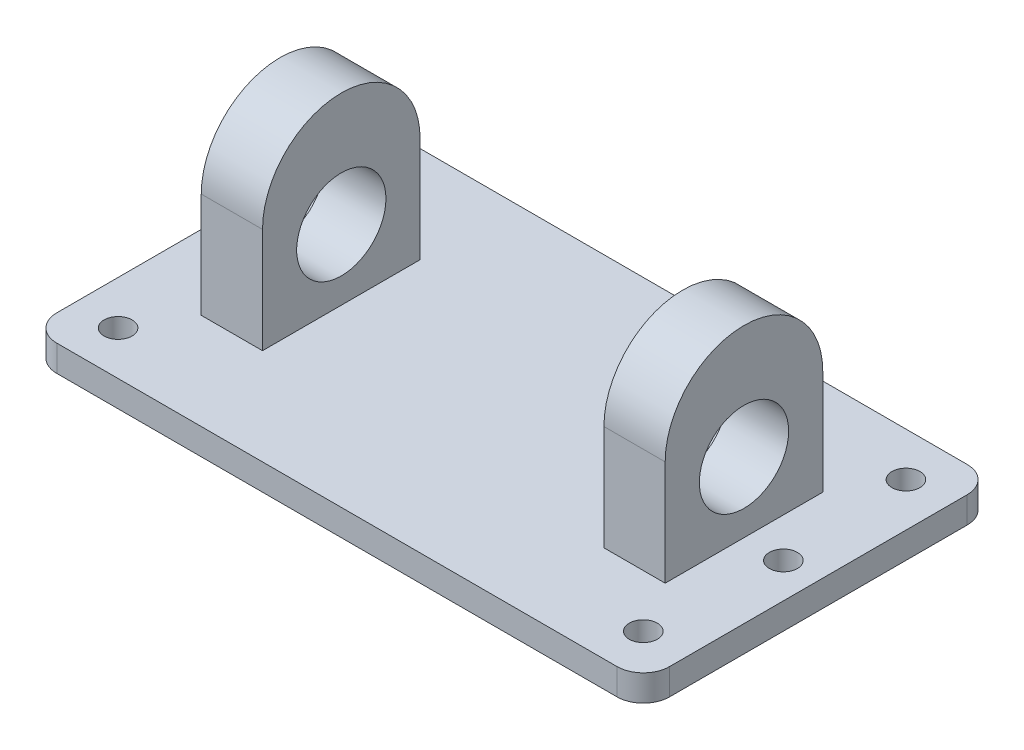
SolidWorks part; units mm, degrees
material "7050-T73510"
ref_plane "前视基准面" through (0, 0, 0) normal (0, 0, 1) x (1, 0, 0)
ref_plane "上视基准面" through (0, 0, 0) normal (0, 1, 0) x (1, 0, 0)
ref_plane "右视基准面" through (0, 0, 0) normal (1, 0, 0) x (0, 0, -1)
sketch "草图1" plane through (0, 0, 0) normal (0, 1, 0) x (1, 0, 0)
  line L1 (-32, -20) -> (32, -20)
  line L2 (-35, -17) -> (-35, 17)
  line L3 (-32, 20) -> (32, 20)
  line L4 (35, -17) -> (35, 17)
  line L5 (-35, -20) -> (35, 20) construction
  line L6 (-35, 20) -> (35, -20) construction
  arc A0 (32, -20) -> (35, -17) centre (32, -17) ccw
  arc A1 (-35, 17) -> (-32, 20) centre (-32, 17) cw
  arc A2 (-32, -20) -> (-35, -17) centre (-32, -17) cw
  arc A3 (32, 20) -> (35, 17) centre (32, 17) cw
  point P0 (0, 0)
  dimension "D3" = 3
  dimension "D1" = 40
  dimension "D2" = 70
extrude "凸台-拉伸1" add sketch "草图1" along normal blind 3
sketch "草图2" plane through (0, 3, 0) normal (0, 1, 0) x (1, 0, 0)
  line L1 (19.5, -9) -> (26.5, -9)
  line L2 (19.5, -9) -> (19.5, 9)
  line L3 (19.5, 9) -> (26.5, 9)
  line L4 (26.5, -9) -> (26.5, 9)
  line L5 (19.5, -9) -> (26.5, 9) construction
  line L6 (19.5, 9) -> (26.5, -9) construction
  point P0 (23, 0)
  dimension "D1" = 23
  dimension "D2" = 7
  dimension "D3" = 18
extrude "凸台-拉伸2" add sketch "草图2" along normal blind 12
mirror "镜向1" about plane through (0, 0, 0) normal (1, 0, 0) of "凸台-拉伸2"
sketch "草图3" plane through (26.5, 0, 0) normal (1, 0, 0) x (0, 0, -1)
  line L0 (-9, 15) -> (9, 15) construction
  circle A0 centre (0, 15) radius 9
extrude "凸台-拉伸3" add sketch "草图3" against normal up to surface (7 mm away) up to face at (19.5, 9, 0)
sketch "草图4" plane through (-26.5, 0, 0) normal (-1, 0, 0) x (0, 0, 1)
  circle A1 centre (0, 15) radius 9
  circle A2 centre (0, 15) radius 9
  dimension "D1" = 0
extrude "凸台-拉伸4" add sketch "草图4" against normal up to surface (7 mm away) up to face at (-19.5, 9, 0)
sketch "草图5" plane through (26.5, 0, 0) normal (1, 0, 0) x (0, 0, -1)
  line L0 (-17, 0) -> (17, 0) construction
  circle A0 centre (0, 11) radius 5
  dimension "D1" = 10
  dimension "D2" = 11
extrude "切除-拉伸1" cut sketch "草图5" against normal through all
sketch "草图6" plane through (0, 3, 0) normal (0, 1, 0) x (1, 0, 0)
  circle A0 centre (-31, 0) radius 1.6
  circle A1 centre (31, 0) radius 1.6
  dimension "D2" = 3.2
  dimension "D3" = 3.2
  dimension "D1" = 31
  dimension "D4" = 31
extrude "切除-拉伸2" cut sketch "草图6" against normal through all
sketch "草图7" plane through (0, 3, 0) normal (0, 1, 0) x (1, 0, 0)
  line L1 (-30, -15) -> (30, -15) construction
  line L2 (-30, -15) -> (-30, 15) construction
  line L3 (-30, 15) -> (30, 15) construction
  line L4 (30, -15) -> (30, 15) construction
  line L5 (-30, -15) -> (30, 15) construction
  line L6 (-30, 15) -> (30, -15) construction
  circle A0 centre (-30, 15) radius 1.6
  circle A1 centre (30, 15) radius 1.6
  circle A2 centre (30, -15) radius 1.6
  circle A3 centre (-30, -15) radius 1.6
  point P0 (0, 0)
  dimension "D3" = 3.2
  dimension "D1" = 30
  dimension "D2" = 60
extrude "切除-拉伸3" cut sketch "草图7" against normal blind 10
sketch "草图8" plane through (26.5, 0, 0) normal (1, 0, 0) x (0, 0, -1)
  circle A2 centre (0, 11) radius 5.1
  circle A3 centre (0, 11) radius 5.1
  dimension "D1" = 0.1
extrude "切除-拉伸4" cut sketch "草图8" against normal through all
